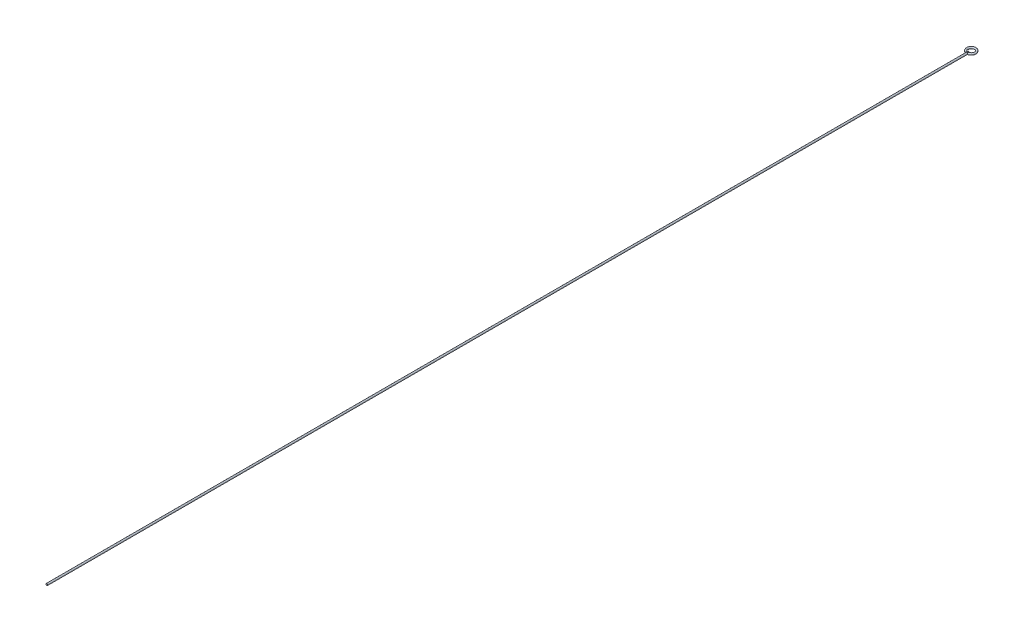
SolidWorks part; units mm, degrees
material "AISI 1010 Steel, hot rolled bar"
ref_plane "Front Plane" through (0, 0, 0) normal (0, 0, 1) x (1, 0, 0)
ref_plane "Top Plane" through (0, 0, 0) normal (0, 1, 0) x (1, 0, 0)
ref_plane "Right Plane" through (0, 0, 0) normal (1, 0, 0) x (0, 0, -1)
sketch "Sketch1" plane through (0, 0, 0) normal (0, 0, 1) x (1, 0, 0)
  circle A0 centre (0, 0) radius 2
  dimension "D1" = 4
extrude "Boss-Extrude1" add sketch "Sketch1" along normal blind 2125 from offset 6
sketch "Sketch4" plane through (0, 0, 0) normal (0, 0, -1) x (-1, 0, 0)
  line L0 (0, 3.776) -> (0, -3.776)
  circle A0 centre (-9, 0) radius 2
  point P4 (0, 0)
  dimension "D1" = 9
revolve "Revolve1" add sketch "Sketch4" angle 360 about L0
sketch "Sketch7" plane through (0, 0, 0) normal (0, 1, 0) x (1, 0, 0)
  circle A0 centre (0, -9) radius 2
  dimension "D1" = 4
  dimension "D2" = 9
extrude "Boss-Extrude2" add sketch "Sketch7" along normal blind 2.1
